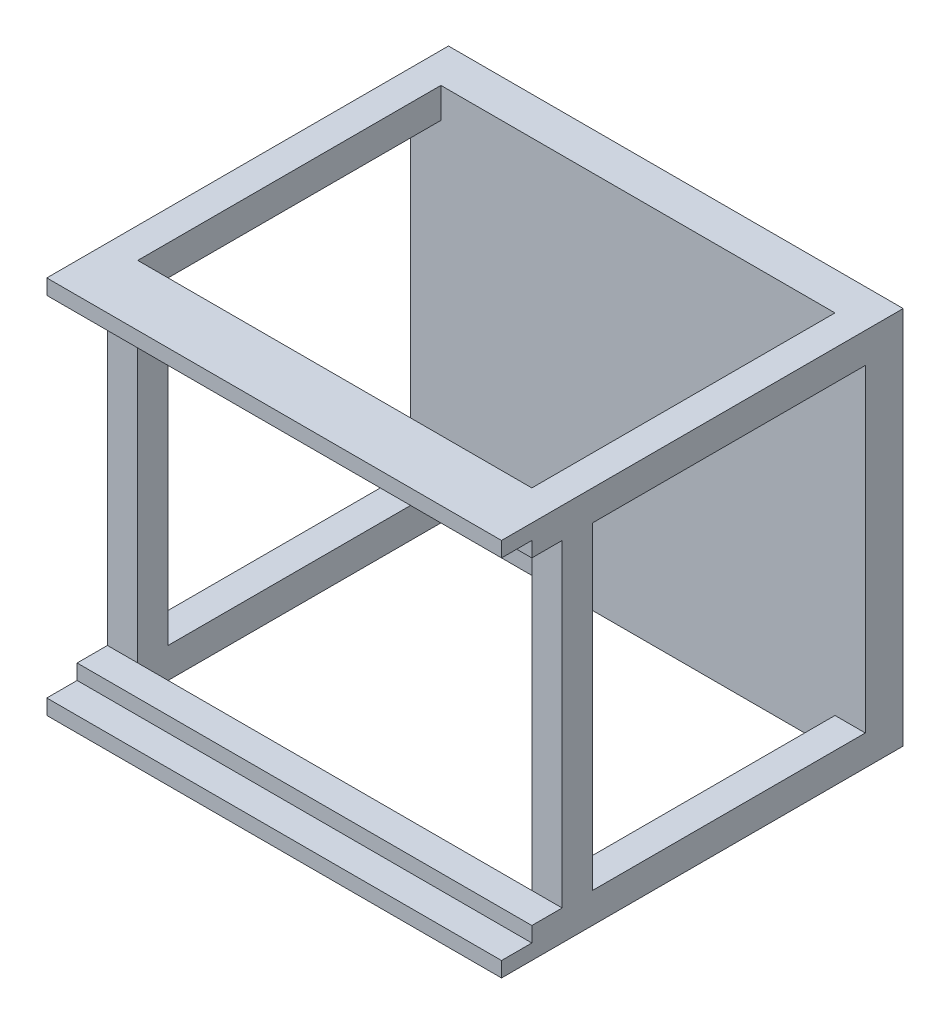
SolidWorks part; units mm, degrees
ref_plane "前视基准面" through (0, 0, 0) normal (0, 0, 1) x (1, 0, 0)
ref_plane "上视基准面" through (0, 0, 0) normal (0, 1, 0) x (1, 0, 0)
ref_plane "右视基准面" through (0, 0, 0) normal (1, 0, 0) x (0, 0, -1)
sketch "草图1" plane through (0, 0, 0) normal (0, 0, 1) x (1, 0, 0)
  line L1 (0, 0) -> (300, 0)
  line L2 (0, 0) -> (0, 250)
  line L3 (0, 250) -> (300, 250)
  line L4 (300, 0) -> (300, 250)
  dimension "D1" = 300
  dimension "D2" = 250
extrude "凸台-拉伸1" add sketch "草图1" along normal blind 25
sketch "草图2" plane through (0, 0, 25) normal (0, 0, 1) x (1, 0, 0)
  line L1 (0, 0) -> (20, 0)
  line L2 (0, 0) -> (0, 20)
  line L3 (0, 20) -> (20, 20)
  line L4 (20, 0) -> (20, 20)
  line L5 (0, 250) -> (20, 250)
  line L6 (0, 250) -> (0, 230)
  line L7 (0, 230) -> (20, 230)
  line L8 (20, 250) -> (20, 230)
  line L9 (300, 250) -> (280, 250)
  line L10 (300, 250) -> (300, 230)
  line L11 (300, 230) -> (280, 230)
  line L12 (280, 250) -> (280, 230)
  line L13 (300, 0) -> (280, 0)
  line L14 (300, 0) -> (300, 20)
  line L15 (300, 20) -> (280, 20)
  line L16 (280, 0) -> (280, 20)
  dimension "D1" = 20
  dimension "D2" = 20
  dimension "D3" = 20
  dimension "D4" = 20
  dimension "D5" = 20
  dimension "D6" = 20
  dimension "D7" = 20
  dimension "D8" = 20
extrude "凸台-拉伸3" add sketch "草图2" along normal blind 200 contours L6 L5 L8 L7 | L2 L1 L4 L3 | L14 L13 L16 L15 | L10 L9 L12 L11
sketch "草图3" plane through (0, 0, 225) normal (0, 0, 1) x (1, 0, 0)
  line L4 (20, 20) -> (0, 20)
  line L5 (0, 20) -> (0, 0)
  line L6 (0, 0) -> (20, 0)
  line L7 (20, 0) -> (20, 20)
  line L8 (20, 20) -> (0, 20)
  line L9 (0, 20) -> (0, 0)
  line L10 (0, 0) -> (20, 0)
  line L11 (20, 0) -> (20, 20)
  dimension "D1" = 0
extrude "凸台-拉伸4" add sketch "草图3" along normal blind 20
sketch "草图4" plane through (0, 0, 225) normal (0, 0, 1) x (1, 0, 0)
  line L4 (300, 20) -> (280, 20)
  line L5 (280, 20) -> (280, 0)
  line L6 (280, 0) -> (300, 0)
  line L7 (300, 0) -> (300, 20)
  line L8 (300, 20) -> (280, 20)
  line L9 (280, 20) -> (280, 0)
  line L10 (280, 0) -> (300, 0)
  line L11 (300, 0) -> (300, 20)
  dimension "D1" = 0
extrude "凸台-拉伸5" add sketch "草图4" along normal blind 20
sketch "草图5" plane through (0, 0, 225) normal (0, 0, 1) x (1, 0, 0)
  line L4 (280, 230) -> (300, 230)
  line L5 (300, 230) -> (300, 250)
  line L6 (300, 250) -> (280, 250)
  line L7 (280, 250) -> (280, 230)
  line L8 (280, 230) -> (300, 230)
  line L9 (300, 230) -> (300, 250)
  line L10 (300, 250) -> (280, 250)
  line L11 (280, 250) -> (280, 230)
  dimension "D1" = 0
extrude "凸台-拉伸6" add sketch "草图5" along normal blind 20
sketch "草图6" plane through (0, 0, 225) normal (0, 0, 1) x (1, 0, 0)
  line L4 (0, 230) -> (20, 230)
  line L5 (20, 230) -> (20, 250)
  line L6 (20, 250) -> (0, 250)
  line L7 (0, 250) -> (0, 230)
  line L8 (0, 230) -> (20, 230)
  line L9 (20, 230) -> (20, 250)
  line L10 (20, 250) -> (0, 250)
  line L11 (0, 250) -> (0, 230)
  dimension "D1" = 0
extrude "凸台-拉伸7" add sketch "草图6" along normal blind 20
sketch "草图8" plane through (20, 0, 0) normal (1, 0, 0) x (0, 0, -1)
  line L0 (-245, 20) -> (-25, 20) construction
  line L1 (-245, 0) -> (-225, 0)
  line L2 (-245, 0) -> (-245, 20)
  line L3 (-245, 20) -> (-225, 20)
  line L4 (-225, 0) -> (-225, 20)
  line L5 (-245, 250) -> (-25, 250) construction
  line L6 (-245, 230) -> (-225, 230)
  line L7 (-245, 230) -> (-245, 250)
  line L8 (-245, 250) -> (-225, 250)
  line L9 (-225, 230) -> (-225, 250)
  dimension "D1" = 20
  dimension "D2" = 20
extrude "凸台-拉伸8" add sketch "草图8" along normal up to next
sketch "草图9" plane through (0, 230, 0) normal (0, -1, 0) x (-1, 0, 0)
  line L0 (0, -245) -> (0, -25) construction
  line L1 (-20, -225) -> (0, -225)
  line L2 (-20, -225) -> (-20, -205)
  line L3 (-20, -205) -> (0, -205)
  line L4 (0, -225) -> (0, -205)
  line L5 (-300, -245) -> (-300, -25) construction
  line L6 (-280, -225) -> (-300, -225)
  line L7 (-280, -225) -> (-280, -205)
  line L8 (-280, -205) -> (-300, -205)
  line L9 (-300, -225) -> (-300, -205)
  dimension "D1" = 20
  dimension "D2" = 20
extrude "凸台-拉伸9" add sketch "草图9" along normal up to next
sketch "草图10" plane through (0, 0, 245) normal (0, 0, 1) x (1, 0, 0)
  line L0 (300, 230) -> (300, 250) construction
  line L1 (0, 250) -> (300, 250)
  line L2 (0, 250) -> (0, 240)
  line L3 (0, 240) -> (300, 240)
  line L4 (300, 250) -> (300, 240)
  line L5 (300, 0) -> (300, 20) construction
  line L6 (0, 0) -> (300, 0)
  line L7 (0, 0) -> (0, 10)
  line L8 (0, 10) -> (300, 10)
  line L9 (300, 0) -> (300, 10)
extrude "凸台-拉伸11" add sketch "草图10" along normal blind 20
